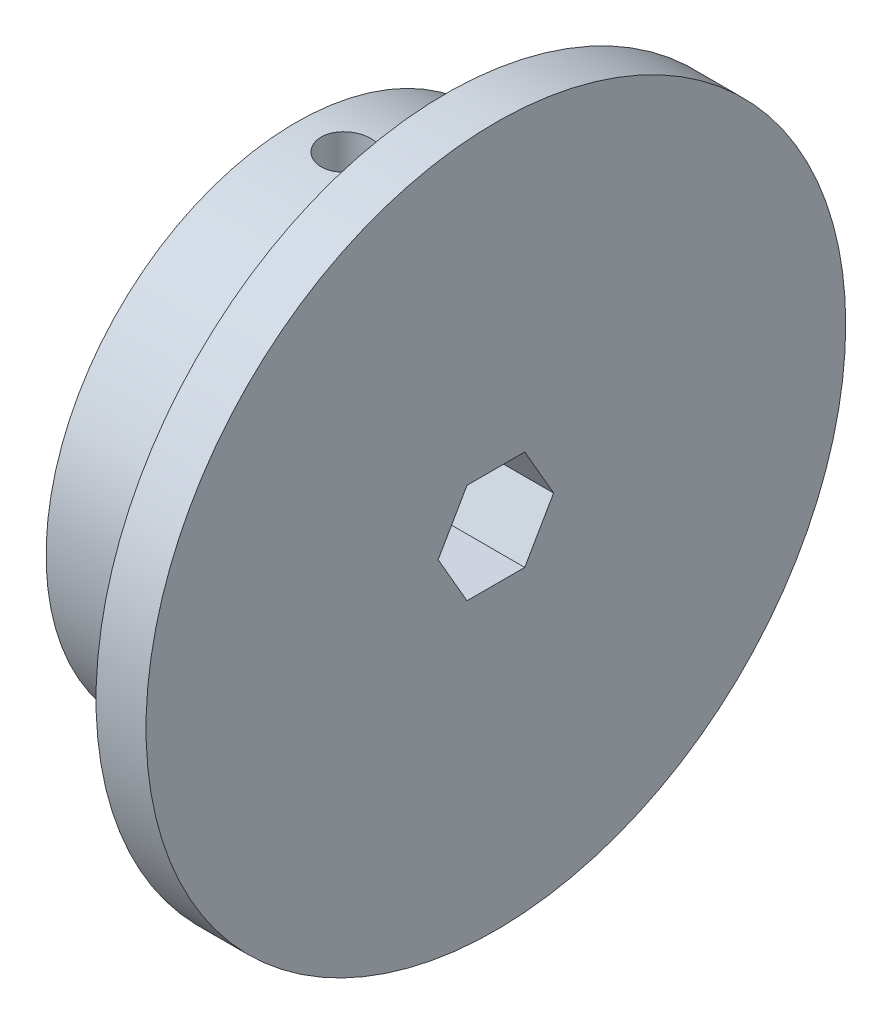
SolidWorks part; units mm, degrees
ref_plane "Front Plane" through (0, 0, 0) normal (0, 0, 1) x (1, 0, 0)
ref_plane "Top Plane" through (0, 0, 0) normal (0, 1, 0) x (1, 0, 0)
ref_plane "Right Plane" through (0, 0, 0) normal (1, 0, 0) x (0, 0, -1)
sketch "Sketch1" plane through (0, 0, 0) normal (1, 0, 0) x (0, 0, -1)
  line L0 (0, 0) -> (-44.45, 0) construction
  line L1 (3.6662, -6.35) -> (7.3323, 0)
  line L2 (7.3323, 0) -> (3.6662, 6.35)
  line L3 (3.6662, 6.35) -> (-3.6662, 6.35)
  line L4 (-3.6662, 6.35) -> (-7.3323, 0)
  line L5 (-7.3323, 0) -> (-3.6662, -6.35)
  line L6 (-3.6662, -6.35) -> (3.6662, -6.35)
  circle A0 centre (0, 0) radius 44.45
  circle A1 centre (0, 0) radius 6.35 construction
  dimension "D1" = 88.9
  dimension "D2" = 12.7
extrude "Boss-Extrude1" add sketch "Sketch1" along normal blind 6.35
sketch "Sketch2" plane through (0, 0, 0) normal (1, 0, 0) x (0, 0, -1)
  line L1 (-7.3323, 0) -> (-3.6662, -6.35)
  line L2 (-3.6662, -6.35) -> (3.6662, -6.35)
  line L3 (3.6662, -6.35) -> (7.3323, 0)
  line L4 (7.3323, 0) -> (3.6662, 6.35)
  line L5 (3.6662, 6.35) -> (-3.6662, 6.35)
  line L6 (-3.6662, 6.35) -> (-7.3323, 0)
  circle A0 centre (0, 0) radius 31.75
  circle A1 centre (0, 0) radius 6.35 construction
  dimension "D1" = 63.5
  dimension "D2" = 12.7
extrude "Boss-Extrude2" add sketch "Sketch2" against normal blind 19.05
sketch "Sketch3" plane through (0, 0, 0) normal (0, 1, 0) x (1, 0, 0)
  line L0 (0, 31.75) -> (0, -31.75) construction
  circle A0 centre (-12.7, 0) radius 3.1396
  dimension "D1" = 6.2792
  dimension "D2" = 12.7
extrude "Cut-Extrude1" cut sketch "Sketch3" against normal through all both and the other way through all
